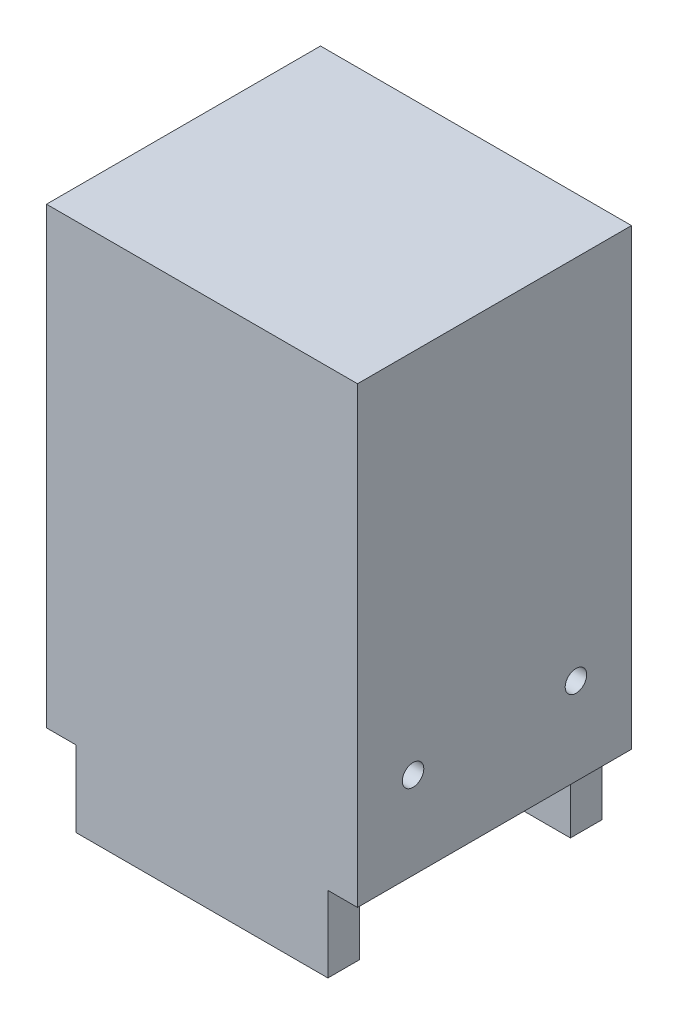
SolidWorks part; units mm, degrees
ref_plane "Front Plane" through (0, 0, 0) normal (0, 0, 1) x (1, 0, 0)
ref_plane "Top Plane" through (0, 0, 0) normal (0, 1, 0) x (1, 0, 0)
ref_plane "Right Plane" through (0, 0, 0) normal (1, 0, 0) x (0, 0, -1)
sketch "Sketch1" plane through (0, 0, 0) normal (0, 0, 1) x (1, 0, 0)
  line L1 (-25, 0) -> (25, 0)
  line L2 (-25, 0) -> (-25, -150)
  line L3 (-25, -150) -> (25, -150)
  line L4 (25, 0) -> (25, -150)
  dimension "D1" = 50
  dimension "D2" = 150
extrude "Boss-Extrude1" add sketch "Sketch1" against normal blind 55
sketch "Sketch2" plane through (25, 0, 0) normal (1, 0, 0) x (0, 0, -1)
  line L0 (55, 0) -> (0, 0) construction
  line L1 (0, -150) -> (0, 0) construction
  circle A0 centre (27.5, -25) radius 10.25
  dimension "D1" = 25
  dimension "D2" = 27.5
extrude "Cut-Extrude1" cut sketch "Sketch2" against normal blind 45 and the other way through all
sketch "Sketch7" plane through (-20, 0, 0) normal (1, 0, 0) x (0, 0, -1)
  line L0 (27.5, -17) -> (27.5, -33) construction
  circle A0 centre (27.5, -25) radius 8
  circle A1 centre (27.5, -17) radius 1
  circle A2 centre (35.5, -25) radius 1
  circle A3 centre (27.5, -33) radius 1
  circle A4 centre (19.5, -25) radius 1
  circle A5 centre (27.5, -25) radius 4.25
  point P14 (27.5, -25)
  dimension "D1" = 16
  dimension "D2" = 2
  dimension "D4" = 8.5
  dimension "D3" = 4
extrude "Cut-Extrude3" cut sketch "Sketch7" against normal blind 10 contours L0 A0 A1 | A0 A1 | A0 L0 A1 | A0 A4 | A0 A4 | L0 A3 A0 | A3 L0 A0 | A0 A3 | A0 A2 | A0 A2 | A5 L0 | L0 A5
sketch "Sketch8" plane through (25, 0, 0) normal (1, 0, 0) x (0, 0, -1)
  line L1 (55, -150) -> (55, 0) construction
  line L3 (0, -150) -> (55, -150)
  line L4 (0, -150) -> (0, -205)
  line L5 (0, -205) -> (55, -205)
  line L6 (55, -150) -> (55, -205)
  circle A1 centre (27.5, -180) radius 10.25
  circle A3 centre (27.5, -25) radius 10.25 construction
  dimension "D1" = 27.5
  dimension "D2" = 155
  dimension "D3" = 25
extrude "Boss-Extrude2" add sketch "Sketch8" against normal blind 50
sketch "Sketch10" plane through (0, 0, 0) normal (0, 0, 1) x (1, 0, 0)
  line L0 (-25, -205) -> (25, -205) construction
  line L5 (17, -205) -> (-17, -205)
  line L6 (17, -205) -> (17, -144.75)
  line L8 (-17, -205) -> (-17, -144.75)
  line L9 (-25, 0) -> (-25, -205) construction
  line L10 (-25, -180) -> (25, -180)
  line L13 (25, -169.75) -> (-25, -169.75)
  line L14 (25, -169.75) -> (25, -190.25)
  line L15 (25, -190.25) -> (-25, -190.25)
  line L16 (-25, -169.75) -> (-25, -190.25)
  line L17 (25, -205) -> (25, 0) construction
  line L18 (0, -180) -> (17, -180)
  line L19 (0, -180) -> (0, -191.25)
  line L20 (0, -191.25) -> (17, -191.25)
  line L21 (17, -180) -> (17, -191.25)
  line L22 (17, -191.25) -> (-17, -191.25)
  line L23 (17, -191.25) -> (17, -169.75)
  line L24 (17, -169.75) -> (-17, -169.75)
  line L25 (-17, -191.25) -> (-17, -169.75)
  line L26 (17, -191.25) -> (-17, -191.25)
  line L27 (17, -191.25) -> (17, -144.75)
  line L28 (17, -144.75) -> (-17, -144.75)
  line L29 (-17, -191.25) -> (-17, -144.75)
  line L30 (-25, -169.75) -> (-17, -169.75)
  line L31 (-25, -169.75) -> (-25, -205)
  line L32 (-25, -205) -> (-17, -205)
  line L33 (-17, -169.75) -> (-17, -205)
  line L34 (25, -169.75) -> (17, -169.75)
  line L35 (25, -169.75) -> (25, -205)
  line L36 (25, -205) -> (17, -205)
  line L37 (17, -169.75) -> (17, -205)
  line L38 (-25, -169.75) -> (25, -169.75)
  line L39 (-25, -169.75) -> (-25, -164.75)
  line L40 (-25, -164.75) -> (25, -164.75)
  line L41 (25, -169.75) -> (25, -164.75)
  line M7 (-25, 0) -> (-25, -205)
  line M8 (-25, -205) -> (25, -205)
  line M9 (25, -205) -> (25, 0)
  dimension "D1" = 8
  dimension "D2" = 8
  dimension "D3" = 11.25
  dimension "D4" = 46.5
  dimension "D5" = 60.25
  dimension "D6" = 5
extrude "Cut-Extrude4" cut sketch "Sketch10" against normal through all contours L20 L22 L8 L6 M8 | L8 L15 M7 M8 | L15 L6 M9 M8 | L15 L8 L10 M7 | L8 L13 L10 M7 | L13 L6 L10 M9 | L15 L10 L6 M9 | L19 L10 L8 L15 | L10 L19 L15 L6 | L6 L13 L8 L10 | L22 L19 L15 L8 | L19 L20 L6 L15 | L29 L40 L27 L28 | L40 L8 L13 L6
sketch "Sketch11" plane through (0, -144.75, 0) normal (0, -1, 0) x (1, 0, 0)
  line L0 (17, -55) -> (17, 0) construction
  line L1 (-17, 0) -> (17, 0)
  line L2 (-17, 0) -> (-17, -13.25)
  line L3 (-17, -13.25) -> (17, -13.25)
  line L4 (17, 0) -> (17, -13.25)
  line L5 (25, -27.5) -> (-30.9131, -27.5) construction
  line L6 (25, -55) -> (25, 0) construction
  line L7 (17, -55) -> (17, -41.75)
  line L8 (-17, -41.75) -> (17, -41.75)
  line L9 (-17, -55) -> (-17, -41.75)
  line L10 (-17, -55) -> (17, -55)
  dimension "D1" = 14.25
extrude "Boss-Extrude4" add sketch "Sketch11" along normal blind 25
sketch "Sketch13" plane through (25, 0, 0) normal (1, 0, 0) x (0, 0, -1)
  line L0 (0, -169.75) -> (0, 0) construction
  line L1 (55, -169.75) -> (0, -169.75)
  line L2 (55, -169.75) -> (55, -159.75)
  line L3 (55, -159.75) -> (0, -159.75)
  line L4 (0, -169.75) -> (0, -159.75)
  dimension "D1" = 10
extrude "Cut-Extrude5" cut sketch "Sketch13" against normal blind 8
ref_plane "Plane2" through (0, 0, 0) normal (1, 0, 0) x (0, 0, -1)
mirror "Mirror2" about plane through (0, 0, 0) normal (1, 0, 0) of "Cut-Extrude5"
sketch "Sketch14" plane through (25, 0, 0) normal (1, 0, 0) x (0, 0, -1)
  line L0 (55, -159.75) -> (0, -159.75) construction
  line L1 (0, -159.75) -> (0, 0) construction
  circle A1 centre (16.5, -148) radius 5.0302
  circle A2 centre (38.5, -148) radius 5.0302
  dimension "D1" = 16.5
  dimension "D2" = 2
  dimension "D3" = 11.75
extrude "Cut-Extrude6" cut sketch "Sketch14" against normal blind 8
mirror "Mirror3" about plane through (0, 0, 0) normal (1, 0, 0) of "Cut-Extrude6"
sketch "Sketch15" plane through (0, 0, 0) normal (0, 0, 1) x (1, 0, 0)
  line L0 (-25, 0) -> (25, 0)
  line L1 (25, 0) -> (0, 0)
  line L3 (-17, -169.75) -> (17, -169.75)
  line L4 (-17, -169.75) -> (-17, -170)
  line L5 (-17, -170) -> (17, -170)
  line L6 (17, -169.75) -> (17, -170)
  line M5 (-17, -169.75) -> (17, -169.75)
  dimension "D1" = 0.25
extrude "Boss-Extrude5" add sketch "Sketch15" against normal blind 13.25 contours L6 L4 L5 M5
ref_plane "Plane3" through (0, 0, -27.5) normal (0, 0, 1) x (1, 0, 0)
mirror "Mirror4" about plane through (0, 0, -27.5) normal (0, 0, 1) of "Boss-Extrude5"
sketch "Sketch16" plane through (0, 0, 0) normal (0, 0, 1) x (1, 0, 0)
  line L7 (-20, -14.75) -> (-18.5, -14.75)
  line L8 (-20, -14.75) -> (-20, -35.25)
  line L9 (-20, -35.25) -> (-18.5, -35.25)
  line L10 (-18.5, -14.75) -> (-18.5, -35.25)
  line L11 (25, 0) -> (-18.5, 0)
  line L12 (25, 0) -> (25, -43.5)
  line L13 (25, -43.5) -> (-18.5, -43.5)
  line L14 (-18.5, 0) -> (-18.5, -43.5)
  line M12 (25, -159.75) -> (25, 0)
  line M13 (25, 0) -> (-25, 0)
  dimension "D1" = 1.5
  dimension "D2" = 43.5
  dimension "D3" = 43.5
extrude "Cut-Extrude7" cut sketch "Sketch16" against normal through all contours L14 L10 L13 M13 M12
sketch "Sketch19" plane through (-20, 0, 0) normal (1, 0, 0) x (0, 0, -1)
  circle A0 centre (27.5, -25) radius 4.25
  circle A1 centre (35.5, -25) radius 1
  circle A2 centre (27.5, -33) radius 1
  circle A3 centre (19.5, -25) radius 1
  circle A4 centre (27.5, -17) radius 1
  point P15 (27.5, -25)
  circle M5 centre (27.5, -25) radius 4.25
  circle M6 centre (27.5, -17) radius 1
  circle M7 centre (35.5, -25) radius 1
  circle M8 centre (27.5, -33) radius 1
  circle M9 centre (19.5, -25) radius 1
  circle M10 centre (27.5, -25) radius 10.25
  dimension "D1" = 4
extrude "Boss-Extrude6" add sketch "Sketch19" along normal blind 1.5 contours M10 M6 M8 M9 M7 M5
sketch "Sketch20" plane through (-18.5, 0, 0) normal (1, 0, 0) x (0, 0, -1)
  line L0 (0, -43.5) -> (9, -43.5)
  line L1 (9, -25) -> (9, -43.5)
  line L2 (9, -43.5) -> (0, -43.5)
  line L3 (46, -25) -> (46, -43.5)
  line L4 (46, -43.5) -> (55, -43.5)
  line L5 (46, -43.5) -> (55, -43.5)
  line L7 (9, -43.5) -> (0, -43.5)
  line L8 (9, -43.5) -> (9, -25)
  line L12 (9, -25) -> (9, -43.5)
  line L13 (9, -43.5) -> (0, -43.5)
  line L15 (0, 0) -> (55, 0)
  line L16 (0, 0) -> (0, -43.5)
  line L17 (0, -43.5) -> (55, -43.5)
  line L18 (55, 0) -> (55, -43.5)
  circle A0 centre (27.5, -25) radius 18.5
  line M6 (0, 0) -> (0, -43.5)
  line M7 (0, -43.5) -> (55, -43.5)
  line M8 (55, -43.5) -> (55, 0)
  line M9 (55, 0) -> (0, 0)
extrude "Cut-Extrude8" cut sketch "Sketch20" against normal through all contours A0 L3 L1 M7 M8 M9 M6
sketch "Sketch21" plane through (25, 0, 0) normal (1, 0, 0) x (0, 0, -1)
  circle A0 centre (16.5, -148) radius 5.0302
  circle A1 centre (16.5, -148) radius 4.5
  circle A2 centre (38.5, -148) radius 4.5
  circle A3 centre (38.5, -148) radius 5.0302
  dimension "D1" = 2
extrude "Boss-Extrude7" add sketch "Sketch21" against normal blind 8
mirror "Mirror5" about plane through (0, 0, 0) normal (1, 0, 0) of "Boss-Extrude7"
sketch "Sketch24" plane through (0, 0, 0) normal (0, 0, 1) x (1, 0, 0)
  line L1 (-25, -159.75) -> (-21, -159.75)
  line L2 (-25, -159.75) -> (-25, -129.75)
  line L3 (-25, -129.75) -> (-21, -129.75)
  line L4 (-21, -159.75) -> (-21, -129.75)
  line L5 (25, -159.75) -> (21, -159.75)
  line L6 (25, -159.75) -> (25, -129.75)
  line L7 (25, -129.75) -> (21, -129.75)
  line L8 (21, -159.75) -> (21, -129.75)
  dimension "D1" = 30
  dimension "D2" = 30
  dimension "D3" = 4
  dimension "D4" = 4
extrude "Cut-Extrude10" cut sketch "Sketch24" against normal through all
sketch "Sketch25" plane through (25, 0, 0) normal (1, 0, 0) x (0, 0, -1)
  line L1 (0, -43.5) -> (55, -43.5)
  line L2 (0, -43.5) -> (0, -129.75)
  line L3 (0, -129.75) -> (55, -129.75)
  line L4 (55, -43.5) -> (55, -129.75)
extrude "Cut-Extrude11" cut sketch "Sketch25" against normal blind 4
sketch "Sketch26" plane through (-18.5, 0, 0) normal (1, 0, 0) x (0, 0, -1)
  line L1 (46, -43.5) -> (9, -43.5)
  line L2 (46, -43.5) -> (46, -25)
  line L3 (46, -25) -> (9, -25)
  line L4 (9, -43.5) -> (9, -25)
  circle A0 centre (27.5, -25) radius 18.5
  circle A1 centre (27.5, -25) radius 4.25
  circle A2 centre (27.5, -33) radius 1
  circle A3 centre (35.5, -25) radius 1
  circle A4 centre (27.5, -17) radius 1
  circle A5 centre (19.5, -25) radius 1
  circle M1 centre (27.5, -25) radius 4.25
  circle M2 centre (35.5, -25) radius 1
  circle M3 centre (19.5, -25) radius 1
  circle M4 centre (27.5, -33) radius 1
  circle M5 centre (27.5, -17) radius 1
  line M6 (9, -25) -> (9, -43.5)
  line M7 (9, -43.5) -> (46, -43.5)
  line M8 (46, -43.5) -> (46, -25)
  arc M9 (46, -25) -> (9, -25) centre (27.5, -25) ccw
extrude "Boss-Extrude8" add sketch "Sketch26" along normal blind 4 contours A0 M6 M7 | A0 L1 M8 | L3 A0 M2 M1 M3 M4 | L3 M9 M3 M1 M2 M5
sketch "Sketch27" plane through (0, 0, 0) normal (0, 0, 1) x (1, 0, 0)
  line L1 (-21, -129.75) -> (-25, -129.75)
  line L2 (-21, -129.75) -> (-21, -6.5)
  line L3 (-21, -6.5) -> (-25, -6.5)
  line L4 (-25, -129.75) -> (-25, -6.5)
extrude "Cut-Extrude12" cut sketch "Sketch27" against normal through all
sketch "Sketch28" plane through (0, 0, 0) normal (0, 0, 1) x (1, 0, 0)
  line L1 (-14.5, -43.5) -> (-21, -43.5)
  line L2 (21, -79) -> (21, -159.75)
  line L3 (21, -159.75) -> (-21, -159.75)
  line L4 (-21, -43.5) -> (-21, -159.75)
  line L5 (21, -43.5) -> (-21, -43.5)
  line L6 (21, -43.5) -> (21, -159.75)
  line L7 (21, -159.75) -> (-21, -159.75)
  line L8 (-21, -43.5) -> (-21, -159.75)
  arc A0 (21, -79) -> (-14.5, -43.5) centre (-14.5, -79) ccw
  point P8 (21, -43.5)
  line M2 (21, -43.5) -> (-21, -43.5)
  line M9 (21, -159.75) -> (21, -43.5)
  dimension "D1" = 35.5
extrude "Cut-Extrude13" cut sketch "Sketch28" against normal through all contours A0 M9 M2
sketch "Sketch29" plane through (0, -170, 0) normal (0, -1, 0) x (1, 0, 0)
  line L5 (-21, -55) -> (-21, 0) construction
  line L6 (21, -55) -> (-21, -55)
  line L7 (21, -55) -> (21, -46)
  line L8 (21, -46) -> (-21, -46)
  line L9 (-21, -55) -> (-21, -46)
  line L10 (21, -55) -> (21, 0) construction
  line L11 (-21, 0) -> (21, 0)
  line L12 (-21, 0) -> (-21, -9)
  line L13 (-21, -9) -> (21, -9)
  line L14 (21, 0) -> (21, -9)
  dimension "D1" = 9
  dimension "D2" = 9
extrude "Cut-Extrude15" cut sketch "Sketch29" against normal through all
sketch "Sketch30" plane through (21, 0, 0) normal (1, 0, 0) x (0, 0, -1)
  circle A0 centre (16.5, -148) radius 4.5
  circle A1 centre (38.5, -148) radius 4.5
  circle A2 centre (16.5, -148) radius 1.45
  circle A3 centre (38.5, -148) radius 1.45
extrude "Boss-Extrude9" add sketch "Sketch30" against normal blind 4
mirror "Mirror6" about plane through (0, 0, 0) normal (1, 0, 0) of "Boss-Extrude9"
sketch "Sketch31" plane through (-21, 0, 0) normal (-1, 0, 0) x (0, 0, 1)
  line L0 (-9, -159.75) -> (-9, -25) construction
  line L1 (-46, -43.5) -> (-9, -43.5)
  line L2 (-46, -43.5) -> (-46, -98.5)
  line L3 (-46, -98.5) -> (-9, -98.5)
  line L4 (-9, -43.5) -> (-9, -98.5)
  dimension "D1" = 55
extrude "Cut-Extrude16" cut sketch "Sketch31" against normal through all
sketch "Sketch32" plane through (-21, 0, 0) normal (-1, 0, 0) x (0, 0, 1)
  line L1 (23.8484, -65.4552) -> (-69.4905, -65.4552)
  line L2 (23.8484, -65.4552) -> (23.8484, -3.3092)
  line L3 (23.8484, -3.3092) -> (-69.4905, -3.3092)
  line L4 (-69.4905, -65.4552) -> (-69.4905, -3.3092)
extrude "Cut-Extrude17" cut sketch "Sketch32" against normal through all
